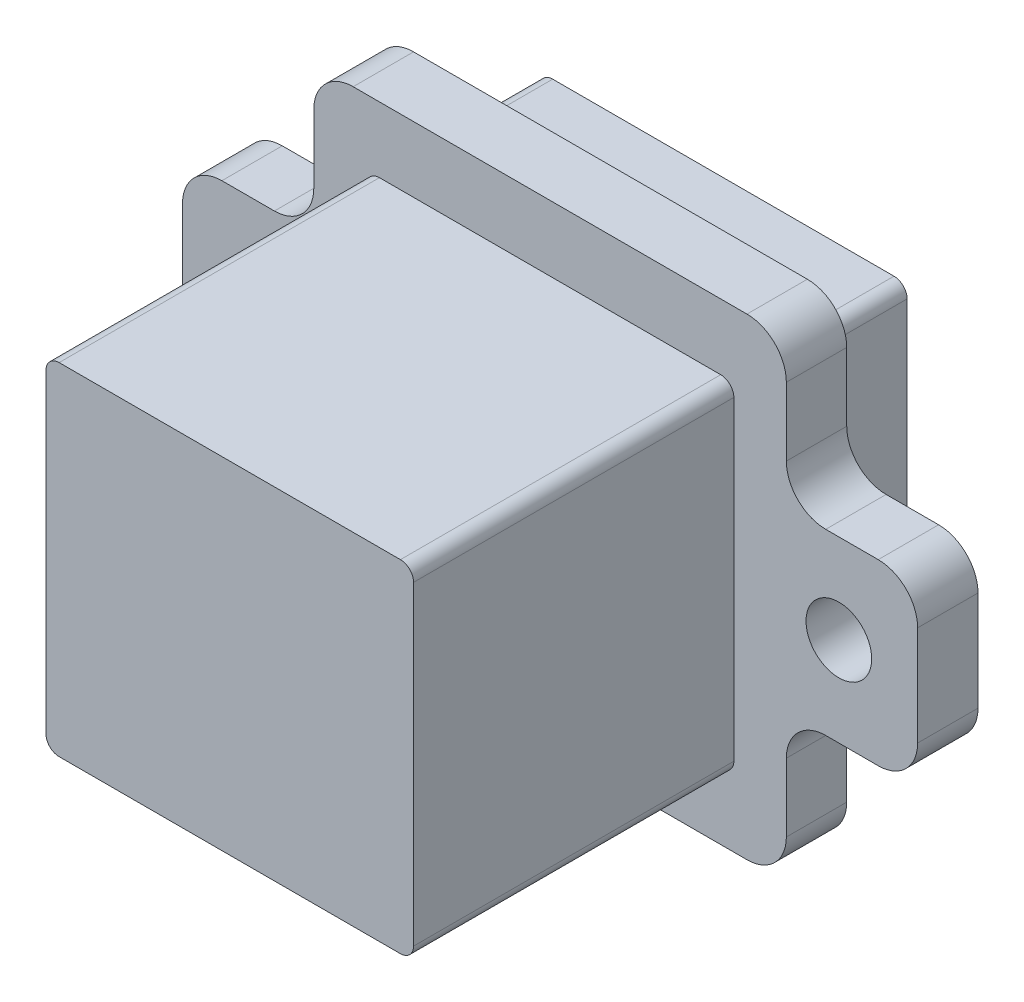
SolidWorks part; units mm, degrees
ref_plane "Спереди" through (0, 0, 0) normal (0, 0, 1) x (1, 0, 0)
ref_plane "Сверху" through (0, 0, 0) normal (0, 1, 0) x (1, 0, 0)
ref_plane "Справа" through (0, 0, 0) normal (1, 0, 0) x (0, 0, -1)
sketch "Эскиз1" plane through (0, 0, 0) normal (0, 0, 1) x (1, 0, 0)
  line L1 (1.5, 0) -> (16.5, 0)
  line L2 (0, 1.5) -> (0, 16.5)
  line L3 (1.5, 18) -> (16.5, 18)
  line L4 (18, 1.5) -> (18, 16.5)
  arc A0 (1.5, 0) -> (0, 1.5) centre (1.5, 1.5) cw
  arc A1 (16.5, 0) -> (18, 1.5) centre (16.5, 1.5) ccw
  arc A2 (16.5, 18) -> (18, 16.5) centre (16.5, 16.5) cw
  arc A3 (0, 16.5) -> (1.5, 18) centre (1.5, 16.5) cw
  point P7 (0, 0)
  point P10 (18, 0)
  point P13 (18, 18)
  point P16 (0, 18)
  dimension "D3" = 1.5
  dimension "D1" = 18
  dimension "D2" = 18
extrude "Бобышка-Вытянуть1" add sketch "Эскиз1" along normal blind 2.3
sketch "Эскиз2" plane through (0, 0, 0) normal (0, 0, -1) x (-1, 0, 0)
  line L0 (-16.5, 18) -> (-1.5, 18) construction
  line L1 (-16, 15.45) -> (-2, 15.45)
  line L2 (-16, 15.45) -> (-16, 2.55)
  line L3 (-16, 2.55) -> (-2, 2.55)
  line L4 (-2, 15.45) -> (-2, 2.55)
  line L5 (0, 16.5) -> (0, 1.5) construction
  point P4 (-9, 15.45)
  point P7 (-9, 18)
  point P8 (-2, 9)
  point P11 (0, 9)
  dimension "D1" = 0
  dimension "D2" = 0
  dimension "D3" = 12.9
  dimension "D4" = 14
extrude "Бобышка-Вытянуть2" add sketch "Эскиз2" along normal blind 4.3
sketch "Эскиз3" plane through (0, 0, -4.3) normal (0, 0, -1) x (-1, 0, 0)
  line L0 (-14.5, 12.55) -> (-12.8315, 13.95)
  line L1 (-12.8315, 13.95) -> (-5.1685, 13.95)
  line L2 (-5.1685, 13.95) -> (-3.5, 12.55)
  line L3 (-3.5, 12.55) -> (-3.5, 4.05)
  line L4 (-3.5, 4.05) -> (-14.5, 4.05)
  line L5 (-14.5, 4.05) -> (-14.5, 12.55)
  line L6 (-2, 15.45) -> (-16, 15.45) construction
  line L7 (-2, 2.55) -> (-2, 15.45) construction
  line L8 (-16, 2.55) -> (-2, 2.55) construction
  line L9 (-2, 15.45) -> (-16, 15.45) construction
  point P6 (-14.8205, 12.6728)
  point P7 (-9, 13.95)
  point P10 (-9, 15.45)
  point P13 (-3.2548, 12.6171)
  point P14 (-3.5322, 4.3195)
  point P19 (-3.869, 4.05)
  dimension "D1" = 0
  dimension "D2" = 100
  dimension "D3" = 50
  dimension "D4" = 8.5
  dimension "D5" = 1.5
  dimension "D6" = 1.5
  dimension "D7" = 1.5
extrude "Вырез-Вытянуть1" cut sketch "Эскиз3" against normal through all
sketch "Эскиз4" plane through (0, 0, 2.3) normal (0, 0, 1) x (1, 0, 0)
  line L0 (16.5, 18) -> (1.5, 18) construction
  line L1 (2, 15.5) -> (16, 15.5)
  line L2 (2, 15.5) -> (2, 2.5)
  line L3 (2, 2.5) -> (16, 2.5)
  line L4 (16, 15.5) -> (16, 2.5)
  line L5 (0, 16.5) -> (0, 1.5) construction
  point P4 (9, 15.5)
  point P7 (9, 18)
  point P8 (2, 9)
  point P11 (0, 9)
  dimension "D1" = 0
  dimension "D2" = 0
  dimension "D3" = 14
  dimension "D4" = 13
extrude "Бобышка-Вытянуть3" add sketch "Эскиз4" along normal blind 12.2
fillet "Скругление1" radius 0.5 8 edges at (16, 2.5, 8.4) (16, 2.55, -2.15) (2, 2.55, -2.15) (2, 2.5, 8.4) (16, 15.45, -2.15) (16, 15.5, 8.4) (2, 15.45, -2.15) (2, 15.5, 8.4)
sketch "Эскиз5" plane through (0, 0, 2.3) normal (0, 0, -1) x (-1, 0, 0)
  line L0 (-5.1685, 13.95) -> (-12.8315, 13.95) construction
  line L1 (-12, 10.5) -> (-6, 10.5)
  line L2 (-12, 10.5) -> (-12, 7.5)
  line L3 (-12, 7.5) -> (-6, 7.5)
  line L4 (-6, 10.5) -> (-6, 7.5)
  line L5 (-2, 3.05) -> (-2, 14.95) construction
  point P4 (-9, 10.5)
  point P7 (-9, 13.95)
  point P8 (-6, 9)
  point P11 (-2, 9)
  dimension "D1" = 0
  dimension "D2" = 0
  dimension "D3" = 6
  dimension "D4" = 3
extrude "Бобышка-Вытянуть4" add sketch "Эскиз5" along normal blind 6.2
sketch "Эскиз6" plane through (0, 0, 0) normal (0, 0, -1) x (-1, 0, 0)
  line L0 (-18, 1.5) -> (-18, 16.5) construction
  line L1 (-18, 5.6) -> (-23, 5.6)
  line L2 (-18, 5.6) -> (-18, 12.4)
  line L3 (-18, 12.4) -> (-23, 12.4)
  line L4 (-23, 5.6) -> (-23, 12.4)
  line L5 (0, 16.5) -> (0, 1.5) construction
  line L6 (0, 12.4) -> (5, 12.4)
  line L7 (0, 12.4) -> (0, 5.6)
  line L8 (0, 5.6) -> (5, 5.6)
  line L9 (5, 12.4) -> (5, 5.6)
  point P6 (-18, 9)
  point P7 (-18, 9)
  point P14 (4.6985, 12.0809)
  dimension "D1" = 0
  dimension "D2" = 28
  dimension "D3" = 6.8
extrude "Бобышка-Вытянуть5" add sketch "Эскиз6" against normal up to surface (2.3 mm away) up to face at (9, 9, 2.3)
sketch "Эскиз7" plane through (0, 0, 0) normal (0, 0, -1) x (-1, 0, 0)
  line L0 (-23, 12.4) -> (-23, 5.6) construction
  line L1 (-1.5, 0) -> (-16.5, 0) construction
  line L2 (-9, 18) -> (-9, 0) construction
  line L3 (-16.5, 18) -> (-1.5, 18) construction
  circle A0 centre (-20, 9) radius 1.25
  circle A1 centre (2, 9) radius 1.25
  point P4 (-23, 9)
  point P7 (-9, 0)
  dimension "D3" = 2.5
  dimension "D1" = 0
  dimension "D2" = 11
extrude "Вырез-Вытянуть2" cut sketch "Эскиз7" against normal through all
fillet "Скругление2" radius 1.5 8 edges at (0, 12.4, 1.15) (-5, 5.6, 1.15) (0, 5.6, 1.15) (18, 5.6, 1.15) (23, 5.6, 1.15) (-5, 12.4, 1.15) (23, 12.4, 1.15) (18, 12.4, 1.15)
fillet "Скругление3" radius 0.3 4 edges at (12, 7.5, -0.8) (6, 7.5, -0.8) (6, 10.5, -0.8) (12, 10.5, -0.8)
